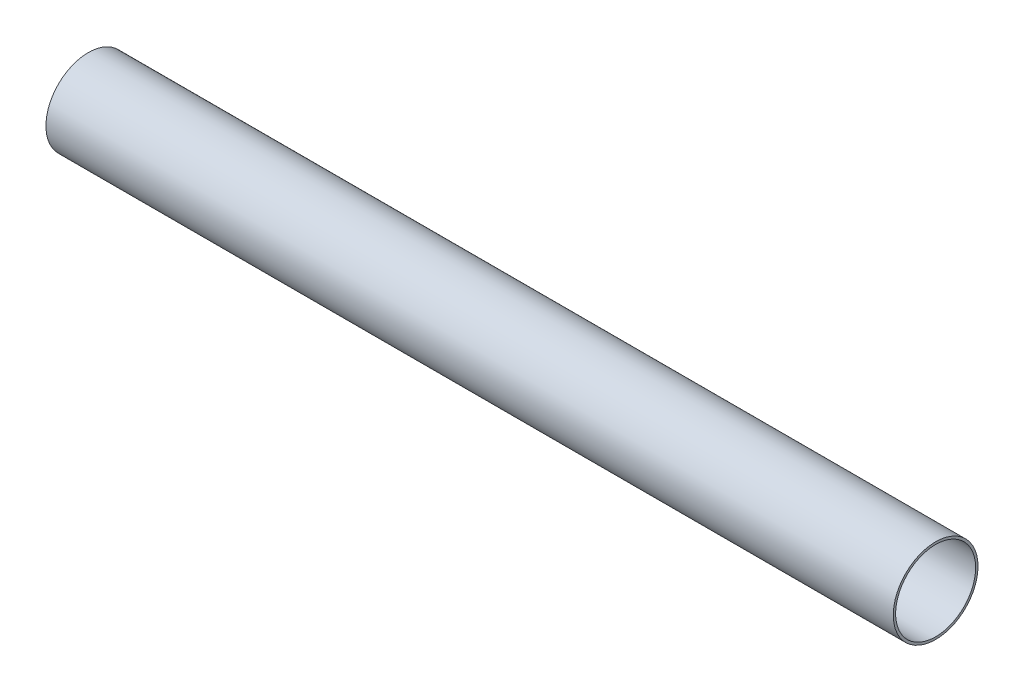
SolidWorks part; units mm, degrees
ref_plane "Front" through (0, 0, 0) normal (0, 0, 1) x (1, 0, 0)
ref_plane "Top" through (0, 0, 0) normal (0, 1, 0) x (1, 0, 0)
ref_plane "Right" through (0, 0, 0) normal (1, 0, 0) x (0, 0, -1)
sketch "Sketch1" plane through (0, 0, 0) normal (1, 0, 0) x (0, 0, -1)
  line L0 (11.9888, 0) -> (12.7, 0) construction
  line L1 (11.9888, 0) -> (12.7, 0) construction
  line L2 (12.3444, 0) -> (12.3444, 1.0672) construction
  circle A0 centre (0, 0) radius 12.7
  circle A1 centre (0, 0) radius 11.9888
  point P4 (12.7, 0)
  point P5 (11.9888, 0)
  dimension "OD" = 25.4
  dimension "D2" = 23.9776
  dimension "D1" = 0.7112
sketch "Sketch2" plane through (0, 0, 0) normal (0, 0, 1) x (1, 0, 0)
  line L0 (-127, 0) -> (127, 0) construction
  point P2 (-95.25, 0)
  point P3 (95.25, 0)
  dimension "D1" = 31.75
  dimension "D2" = 31.75
sketch "Sketch3" plane through (0, 0, 0) normal (1, 0, 0) x (0, 0, -1)
  circle A0 centre (0, 0) radius 11.9888 construction
  circle A1 centre (0, 0) radius 12.7 construction
  circle A2 centre (0, 0) radius 11.9888
  circle A3 centre (0, 0) radius 12.7
extrude "Boss-Extrude1" add sketch "Sketch3" along normal mid plane 254
sketch "Sketch4" plane through (0, 0, 0) normal (0, 0, 1) x (1, 0, 0)
  line L0 (-127, 12.7) -> (-127, -12.7) construction
  line L1 (-127, 12.7) -> (-127, -12.7)
  dimension "D1" = 25.4
equation "\"D1@Boss-Extrude1\"=\"Length@Sketch2\""
equation "\"D1@Sketch2\"=\"OD@Sketch1\"*1.25"
equation "\"D2@Sketch2\"=\"D1@Sketch2\""
